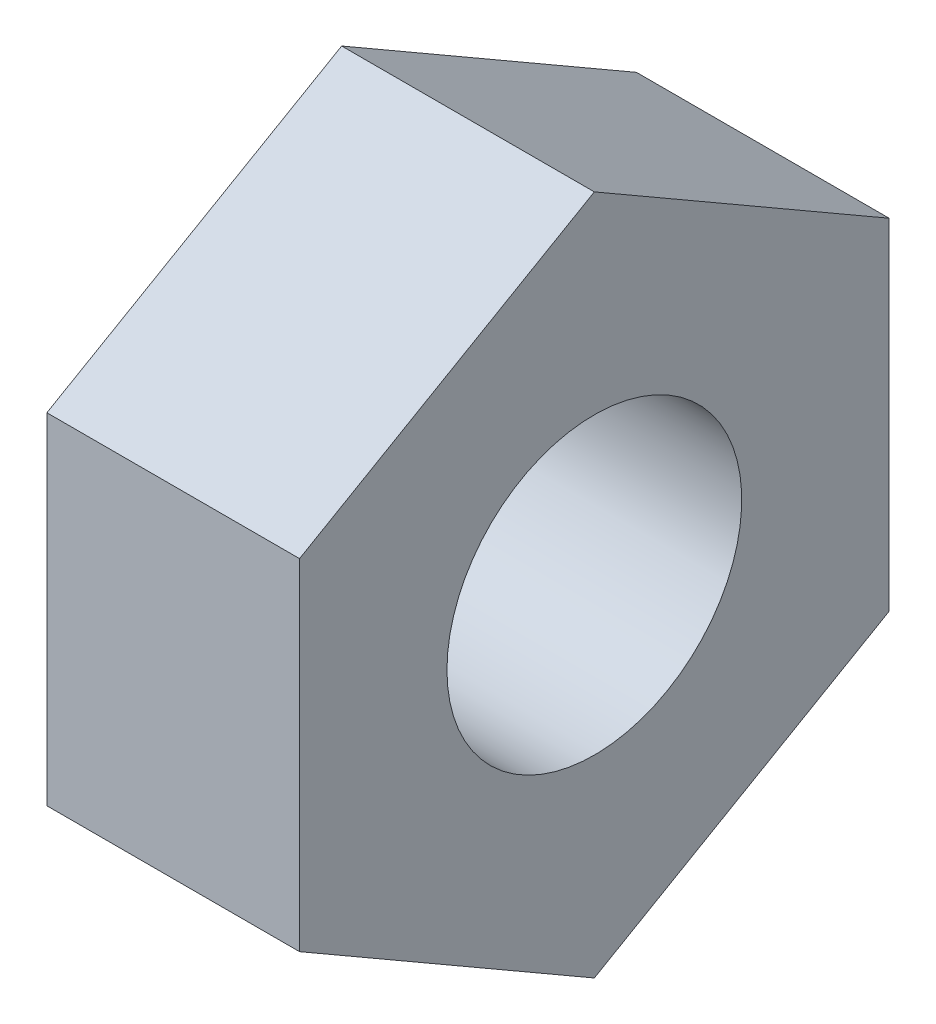
SolidWorks part; units mm, degrees
material "Free-Cutting Brass, UNS C36000"
ref_plane "Front Plane" through (0, 0, 0) normal (0, 0, 1) x (1, 0, 0)
ref_plane "Top Plane" through (0, 0, 0) normal (0, 1, 0) x (1, 0, 0)
ref_plane "Right Plane" through (0, 0, 0) normal (1, 0, 0) x (0, 0, -1)
sketch "Sketch1" plane through (0, 0, 0) normal (1, 0, 0) x (0, 0, -1)
  line L0 (0, 55) -> (0, -55) construction
  line L1 (3.5, -2.0207) -> (3.5, 2.0207)
  line L2 (3.5, 2.0207) -> (0, 4.0415)
  line L3 (0, 4.0415) -> (-3.5, 2.0207)
  line L4 (-3.5, 2.0207) -> (-3.5, -2.0207)
  line L5 (-3.5, -2.0207) -> (0, -4.0415)
  line L6 (0, -4.0415) -> (3.5, -2.0207)
  circle A0 centre (0, 0) radius 3.5 construction
  dimension "D1" = 7
extrude "Hex_Head" add sketch "Sketch1" along normal blind 3
sketch "Sketch2" plane through (0, 0, 0) normal (-1, 0, 0) x (0, 0, 1)
  circle A0 centre (0, 0) radius 1.75
  dimension "D1" = 3.5
extrude "Cut-Extrude1" cut sketch "Sketch2" against normal blind 3
